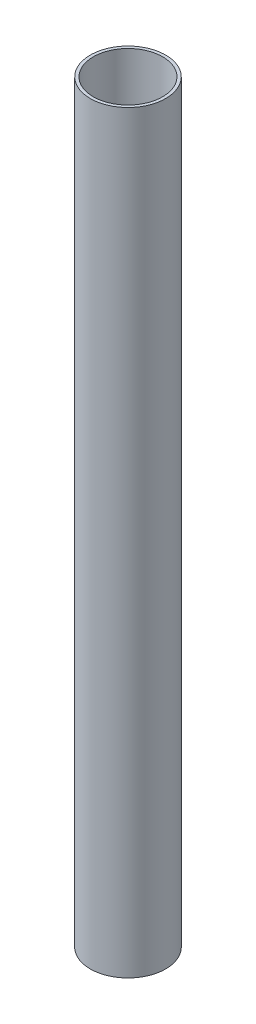
SolidWorks part; units mm, degrees
ref_plane "Front Plane" through (0, 0, 0) normal (0, 0, 1) x (1, 0, 0)
ref_plane "Top Plane" through (0, 0, 0) normal (0, 1, 0) x (1, 0, 0)
ref_plane "Right Plane" through (0, 0, 0) normal (1, 0, 0) x (0, 0, -1)
sketch "Sketch1" plane through (0, 0, 0) normal (0, 1, 0) x (1, 0, 0)
  circle A0 centre (0, 0) radius 1.5875
  point P3 (0, 0)
  dimension "D1" = 3.175
extrude "Boss-Extrude1" add sketch "Sketch1" along normal blind 31.75
shell "Shell4" thickness 0.127
